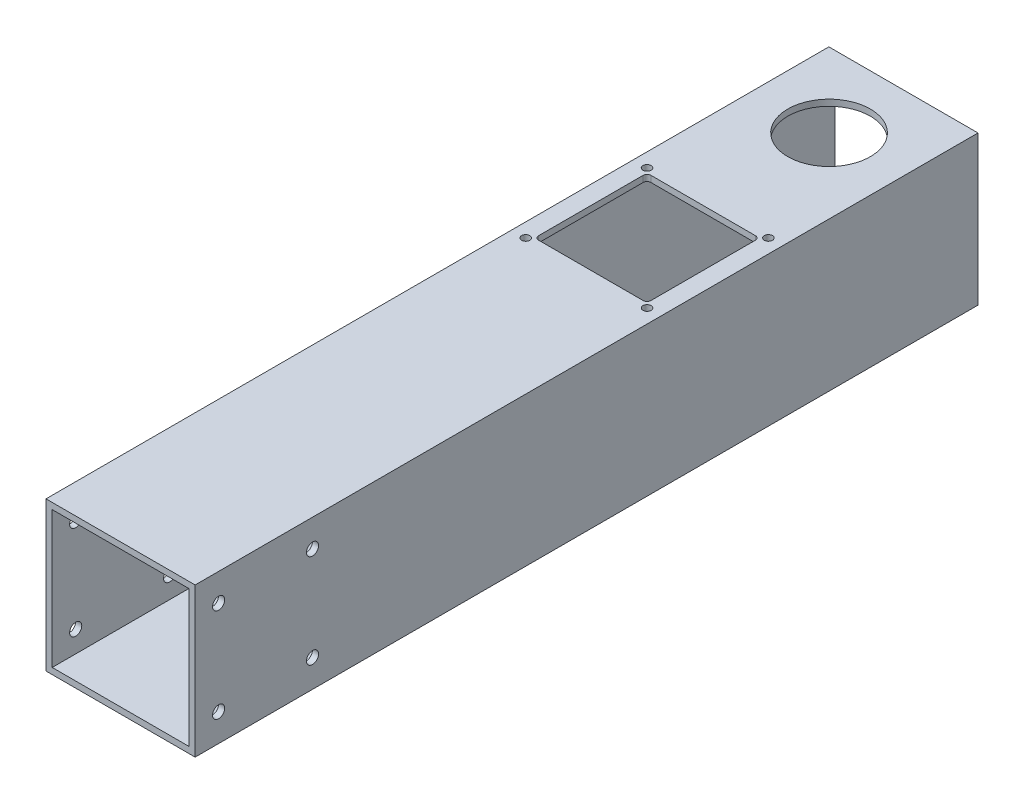
SolidWorks part; units mm, degrees
ref_plane "Front Plane" through (0, 0, 0) normal (0, 0, 1) x (1, 0, 0)
ref_plane "Top Plane" through (0, 0, 0) normal (0, 1, 0) x (1, 0, 0)
ref_plane "Right Plane" through (0, 0, 0) normal (1, 0, 0) x (0, 0, -1)
sketch "Sketch1" plane through (0, 0, 0) normal (0, 0, 1) x (1, 0, 0)
  line L0 (-34.925, 34.925) -> (34.925, 34.925)
  line L1 (-38.1, -38.1) -> (38.1, -38.1)
  line L2 (-38.1, -38.1) -> (-38.1, 38.1)
  line L3 (-38.1, 38.1) -> (38.1, 38.1)
  line L4 (38.1, -38.1) -> (38.1, 38.1)
  line L5 (-38.1, -38.1) -> (38.1, 38.1) construction
  line L6 (-38.1, 38.1) -> (38.1, -38.1) construction
  line L7 (34.925, -34.925) -> (34.925, 34.925)
  line L8 (-34.925, -34.925) -> (34.925, -34.925)
  line L9 (-34.925, -34.925) -> (-34.925, 34.925)
  point P0 (0, 0)
  dimension "D1" = 76.2
  dimension "D2" = 3.175
extrude "Boss-Extrude1" add sketch "Sketch1" along normal mid plane 400 contours L9 L8 L7 L0 | L3 L4 L1 L2
sketch "Sketch4" plane through (38.1, 0, 0) normal (1, 0, 0) x (0, 0, -1)
  line L0 (-200, -38.1) -> (-200, 38.1) construction
  line L1 (-188, 24) -> (-140, 24) construction
  line L2 (-188, 24) -> (-188, -24) construction
  line L3 (-188, -24) -> (-140, -24) construction
  line L4 (-140, 24) -> (-140, -24) construction
  line L5 (-188, 24) -> (-140, -24) construction
  line L6 (-188, -24) -> (-140, 24) construction
  circle A0 centre (-188, 24) radius 3.1
  circle A1 centre (-140, 24) radius 3.1
  circle A2 centre (-140, -24) radius 3.1
  circle A3 centre (-188, -24) radius 3.1
  point P0 (-164, 0)
  point P9 (0, 0)
  dimension "D4" = 6.2
  dimension "D1" = 48
  dimension "D2" = 48
  dimension "D3" = 12
  dimension "D5" = 4
extrude "Cut-Extrude2" cut sketch "Sketch4" against normal through all contours A1 | A0 | A2 | A3
sketch "Sketch5" plane through (0, 38.1, 0) normal (0, 1, 0) x (1, 0, 0)
  line L0 (0, 200) -> (0, -200) construction
  line L1 (-38.1, 200) -> (38.1, 200) construction
  line L2 (-38.1, -200) -> (38.1, -200) construction
  line L4 (-31, 100) -> (31, 100) construction
  line L5 (-31, 100) -> (-31, 38) construction
  line L6 (-31, 38) -> (31, 38) construction
  line L7 (31, 100) -> (31, 38) construction
  line L8 (-31, 100) -> (31, 38) construction
  line L9 (-31, 38) -> (31, 100) construction
  line L10 (-28.7, 97.7) -> (28.7, 97.7)
  line L11 (-28.7, 97.7) -> (-28.7, 40.3)
  line L12 (-28.7, 40.3) -> (28.7, 40.3)
  line L13 (28.7, 97.7) -> (28.7, 40.3)
  line L14 (-28.7, 97.7) -> (28.7, 40.3) construction
  line L15 (-28.7, 40.3) -> (28.7, 97.7) construction
  circle A0 centre (-31, 100) radius 2.1
  circle A1 centre (31, 100) radius 2.1
  circle A2 centre (31, 38) radius 2.1
  circle A3 centre (-31, 38) radius 2.1
  point P6 (0, 69)
  point P21 (0, 69)
  dimension "D3" = 4.2
  dimension "D1" = 62
  dimension "D2" = 62
  dimension "D5" = 100
  dimension "D6" = 57.4
  dimension "D7" = 57.4
  dimension "D4" = 4
extrude "Cut-Extrude3" cut sketch "Sketch5" against normal up to next contours A2 | A0 | A3 | A1 | L11 L10 L13 L12
fillet "Fillet1" radius 2 4 edges at (-28.7, 36.5125, -40.3) (28.7, 36.5125, -40.3) (28.7, 36.5125, -97.7) (-28.7, 36.5125, -97.7)
sketch "Sketch6" plane through (0, 38.1, 0) normal (0, 1, 0) x (1, 0, 0)
  line L0 (-38.1, 200) -> (38.1, 200) construction
  circle A0 centre (0, 162) radius 21.1
  point P2 (0, 0)
  dimension "D1" = 42.2
  dimension "D2" = 38
extrude "Cut-Extrude4" cut sketch "Sketch6" against normal through all contours A0
